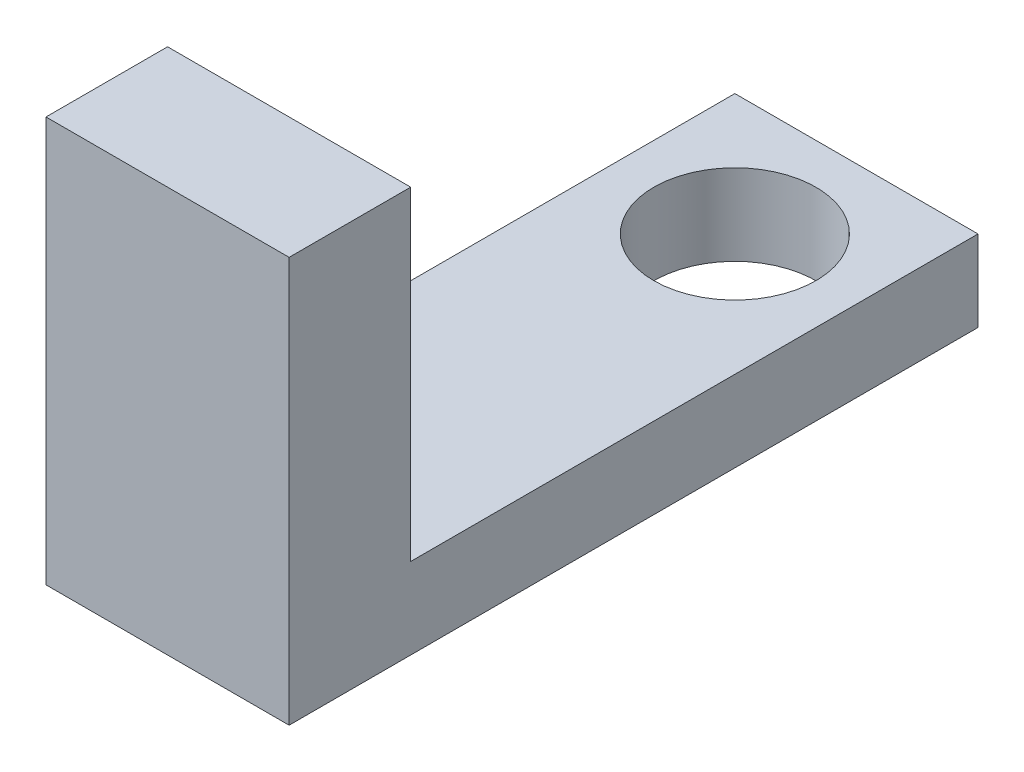
SolidWorks part; units mm, degrees
ref_plane "Front Plane" through (0, 0, 0) normal (0, 0, 1) x (1, 0, 0)
ref_plane "Top Plane" through (0, 0, 0) normal (0, 1, 0) x (1, 0, 0)
ref_plane "Right Plane" through (0, 0, 0) normal (1, 0, 0) x (0, 0, -1)
sketch "Sketch1" plane through (0, 0, 0) normal (1, 0, 0) x (0, 0, -1)
  line L0 (0, 40) -> (0, 0)
  line L1 (0, 0) -> (70, 0)
  line L2 (70, 0) -> (70, -10)
  line L3 (70, -10) -> (-15, -10)
  line L4 (-15, -10) -> (-15, 40)
  line L5 (-15, 40) -> (0, 40)
  dimension "D1" = 10
  dimension "D2" = 70
  dimension "D3" = 85
  dimension "D4" = 50
extrude "Boss-Extrude1" add sketch "Sketch1" along normal blind 30
sketch "Sketch2" plane through (0, 0, 0) normal (0, 1, 0) x (1, 0, 0)
  line L0 (0, 70) -> (0, 0) construction
  line L1 (30, 70) -> (0, 70) construction
  circle A0 centre (15, 55) radius 10
  dimension "D1" = 20
  dimension "D2" = 15
  dimension "D3" = 15
extrude "Cut-Extrude1" cut sketch "Sketch2" against normal blind 10
